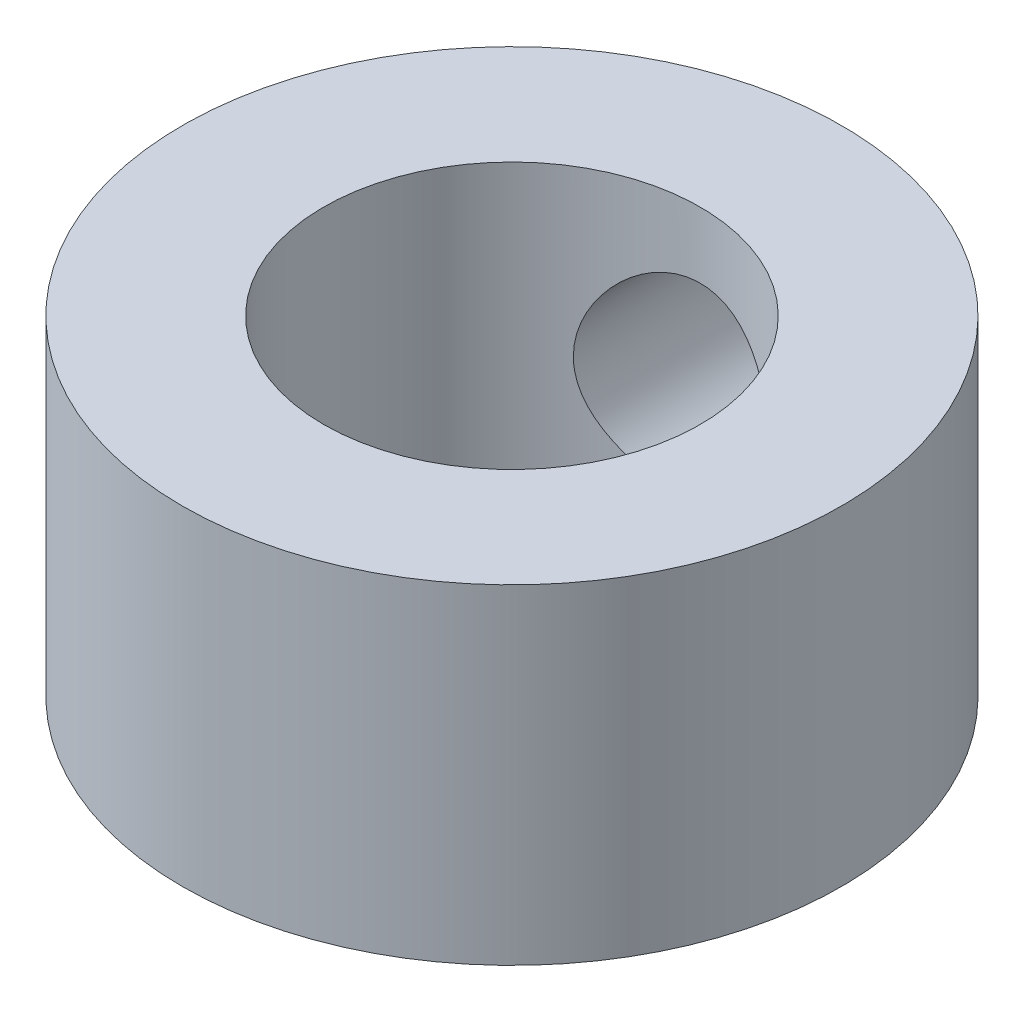
SolidWorks part; units mm, degrees
material "AISI 1020"
ref_plane "Front Plane" through (0, 0, 0) normal (0, 0, 1) x (1, 0, 0)
ref_plane "Top Plane" through (0, 0, 0) normal (0, 1, 0) x (1, 0, 0)
ref_plane "Right Plane" through (0, 0, 0) normal (1, 0, 0) x (0, 0, -1)
sketch "Sketch1" plane through (0, 0, 0) normal (0, 1, 0) x (1, 0, 0)
  circle A0 centre (0, 0) radius 7
  dimension "D1" = 14
extrude "Boss-Extrude1" add sketch "Sketch1" along normal blind 7
hole_wizard "Ø8.0 (8) Diameter Hole1" positions "Sketch2" profile "Sketch3" hole size "Ø8.0" standard "ANSI Metric" end condition through all
sketch "Sketch2" plane through (0, 7, 0) normal (0, 1, 0) x (1, 0, 0)
  point P0 (0, 0)
sketch "Sketch3" plane through (0, 7, 0) normal (1, 0, 0) x (0, 0, 1)
  line L0 (0, 0) -> (0, 7)
  line L1 (0, 7) -> (4, 7)
  line L2 (4, 7) -> (4, 0)
  line L5 (4, 0) -> (0, 0)
  line L11 (0, -6.35) -> (0, 107.95) construction
  dimension "Thru Hole Dia." = 8
  dimension "Thru Hole Depth" = 7
ref_plane "Plane1" through (0, 0, -7) normal (0, 0, -1) x (-1, 0, 0)
sketch "Sketch11" plane through (0, 0, -7) normal (0, 0, -1) x (-1, 0, 0)
  line L0 (4, 7) -> (-4, 7) construction
  line L2 (7, 0) -> (7, 7) construction
  circle A0 centre (0, 3.5) radius 2.1
  dimension "D1" = 4.2
  dimension "D2" = 3.5
  dimension "D3" = 7
extrude "Cut-Extrude1" cut sketch "Sketch11" against normal blind 7
